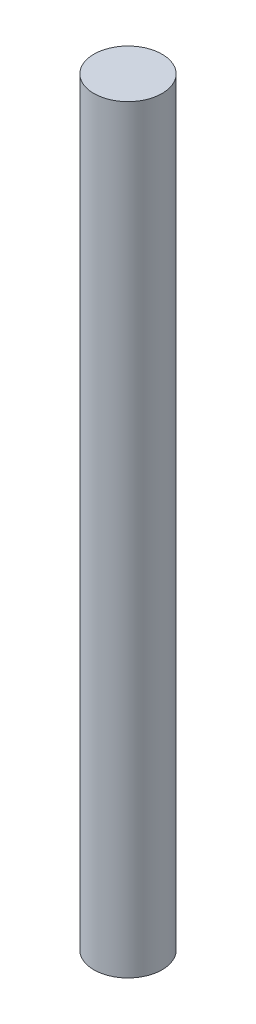
SolidWorks part; units mm, degrees
ref_plane "前视基准面" through (0, 0, 0) normal (0, 0, 1) x (1, 0, 0)
ref_plane "上视基准面" through (0, 0, 0) normal (0, 1, 0) x (1, 0, 0)
ref_plane "右视基准面" through (0, 0, 0) normal (1, 0, 0) x (0, 0, -1)
sketch "草图1" plane through (0, 0, 0) normal (0, 1, 0) x (1, 0, 0)
  circle A0 centre (0, 0) radius 1.5
  dimension "D1" = 3
extrude "凸台-拉伸1" add sketch "草图1" along normal blind 33.4
